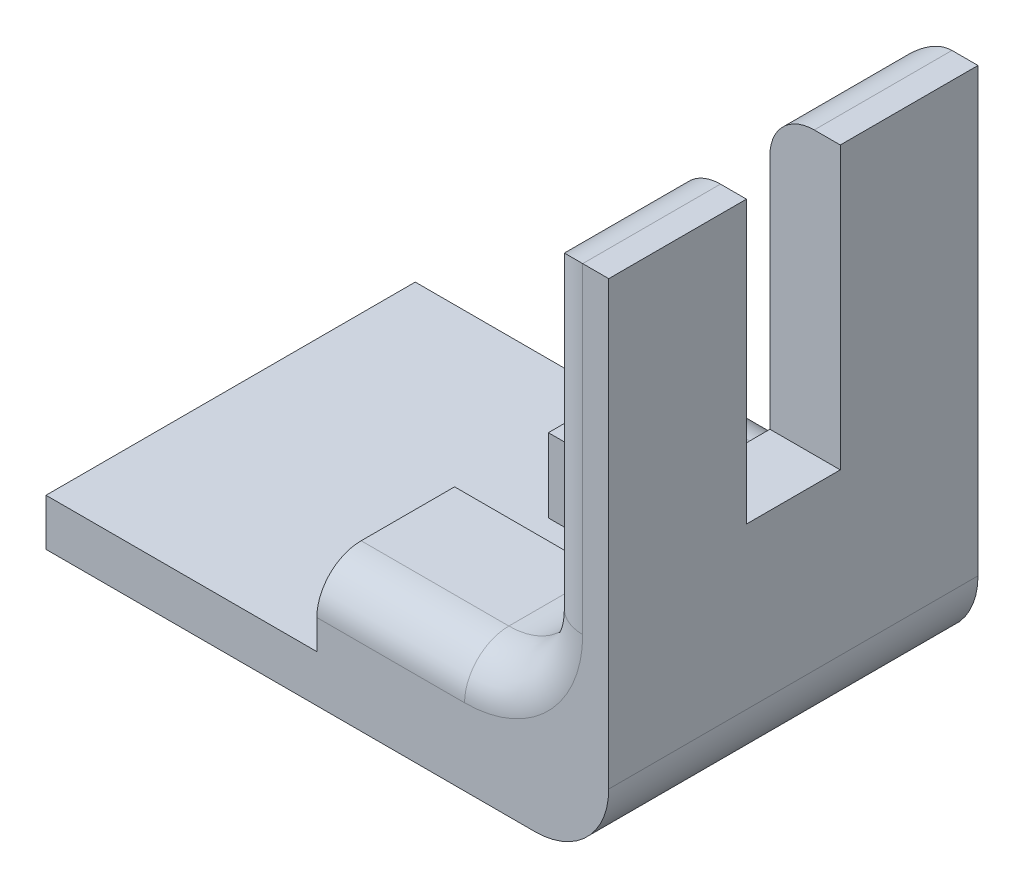
SolidWorks part; units mm, degrees
ref_plane "Front Plane" through (0, 0, 0) normal (0, 0, 1) x (1, 0, 0)
ref_plane "Top Plane" through (0, 0, 0) normal (0, 1, 0) x (1, 0, 0)
ref_plane "Right Plane" through (0, 0, 0) normal (1, 0, 0) x (0, 0, -1)
sketch "Sketch1" plane through (0, 0, 0) normal (0, 1, 0) x (1, 0, 0)
  line L1 (-55.5357, 11.4501) -> (20.6643, 11.4501)
  line L2 (-55.5357, 11.4501) -> (-55.5357, -38.5499)
  line L3 (-55.5357, -38.5499) -> (20.6643, -38.5499)
  line L4 (20.6643, 11.4501) -> (20.6643, -38.5499)
  dimension "D1" = 76.2
  dimension "D2" = 50
extrude "Boss-Extrude1" add sketch "Sketch1" along normal blind 6.35
sketch "Sketch2" plane through (0, 6.35, 0) normal (0, 1, 0) x (1, 0, 0)
  line L0 (-55.5357, -38.5499) -> (20.6643, -38.5499) construction
  line L1 (20.6643, 11.4501) -> (11.1393, 11.4501)
  line L2 (20.6643, 11.4501) -> (20.6643, -38.5499)
  line L3 (20.6643, -38.5499) -> (11.1393, -38.5499)
  line L4 (11.1393, 11.4501) -> (11.1393, -38.5499)
  dimension "D1" = 9.525
extrude "Boss-Extrude2" add sketch "Sketch2" along normal blind 63.5
sketch "Sketch3" plane through (11.1393, 0, 0) normal (-1, 0, 0) x (0, 0, 1)
  line L0 (13.5499, 6.35) -> (13.5499, 69.85) construction
  line L1 (-11.4501, 6.35) -> (38.5499, 6.35) construction
  line L2 (-11.4501, 69.85) -> (38.5499, 69.85) construction
  line L4 (19.8999, 31.75) -> (7.1999, 31.75)
  line L5 (19.8999, 31.75) -> (19.8999, 69.85)
  line L6 (19.8999, 69.85) -> (7.1999, 69.85)
  line L7 (7.1999, 31.75) -> (7.1999, 69.85)
  line L8 (19.8999, 31.75) -> (7.1999, 69.85) construction
  line L9 (19.8999, 69.85) -> (7.1999, 31.75) construction
  point P6 (13.5499, 50.8)
  dimension "D1" = 38.1
  dimension "D2" = 12.7
extrude "Cut-Extrude1" cut sketch "Sketch3" against normal blind 63.5
sketch "Sketch4" plane through (0, 6.35, 0) normal (0, 1, 0) x (1, 0, 0)
  line L0 (-55.5357, -38.5499) -> (11.1393, -38.5499) construction
  line L1 (11.1393, 11.4501) -> (-18.8607, 11.4501)
  line L2 (11.1393, 11.4501) -> (11.1393, -38.5499)
  line L3 (11.1393, -38.5499) -> (-18.8607, -38.5499)
  line L4 (-18.8607, 11.4501) -> (-18.8607, -38.5499)
  dimension "D1" = 30
extrude "Boss-Extrude3" add sketch "Sketch4" along normal blind 10
sketch "Sketch5" plane through (0, 16.35, 0) normal (0, 1, 0) x (1, 0, 0)
  line L0 (11.1393, -13.5499) -> (-18.8607, -13.5499) construction
  line L1 (11.1393, -38.5499) -> (11.1393, 11.4501) construction
  line L2 (-18.8607, 11.4501) -> (-18.8607, -38.5499) construction
  line L4 (-18.8607, -19.8999) -> (11.1393, -19.8999)
  line L5 (-18.8607, -19.8999) -> (-18.8607, -7.1999)
  line L6 (-18.8607, -7.1999) -> (11.1393, -7.1999)
  line L7 (11.1393, -19.8999) -> (11.1393, -7.1999)
  line L8 (-18.8607, -19.8999) -> (11.1393, -7.1999) construction
  line L9 (-18.8607, -7.1999) -> (11.1393, -19.8999) construction
  point P6 (-3.8607, -13.5499)
  dimension "D1" = 12.7
extrude "Cut-Extrude2" cut sketch "Sketch5" against normal blind 10
fillet "Fillet2" radius 10 2 edges at (11.1393, 16.35, -2.1251) (11.1393, 16.35, 29.2249)
fillet "Fillet3" radius 6 8 edges at (-8.8607, 16.35, -11.4501) (8.2104, 19.2789, -11.4501) (-8.8607, 16.35, 38.5499) (8.2104, 19.2789, 38.5499) (11.1393, 69.85, 29.2249) (11.1393, 69.85, -2.1251)
fillet "Fillet4" radius 10 1 edges at (20.6643, 0, 13.5499)
